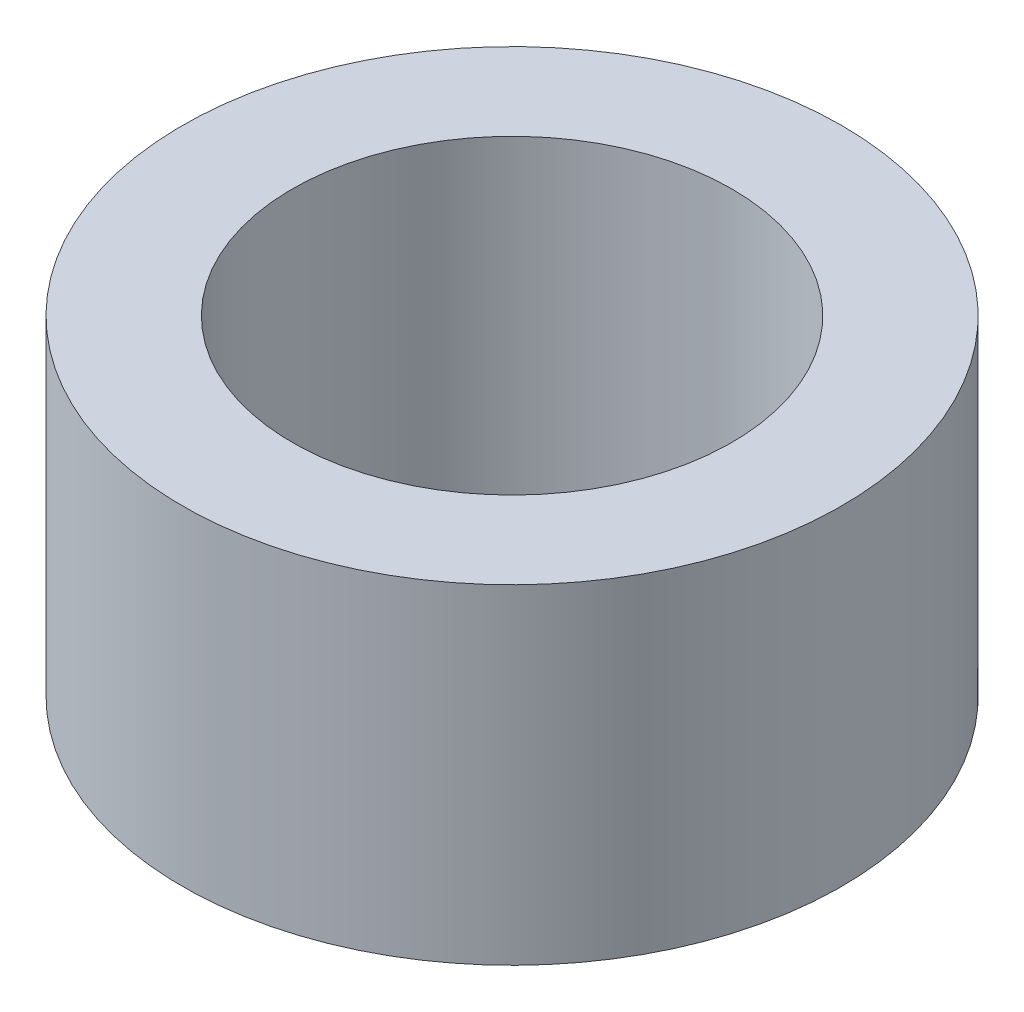
SolidWorks part; units mm, degrees
material "Brass"
ref_plane "Front Plane" through (0, 0, 0) normal (0, 0, 1) x (1, 0, 0)
ref_plane "Top Plane" through (0, 0, 0) normal (0, 1, 0) x (1, 0, 0)
ref_plane "Right Plane" through (0, 0, 0) normal (1, 0, 0) x (0, 0, -1)
sketch "Sketch1" plane through (0, 0, 0) normal (0, 1, 0) x (1, 0, 0)
  circle A0 centre (0, 0) radius 9.525
  circle A1 centre (0, 0) radius 6.35
  dimension "D1" = 19.05
  dimension "D2" = 12.7
extrude "Boss-Extrude1" add sketch "Sketch1" along normal mid plane 9.525
